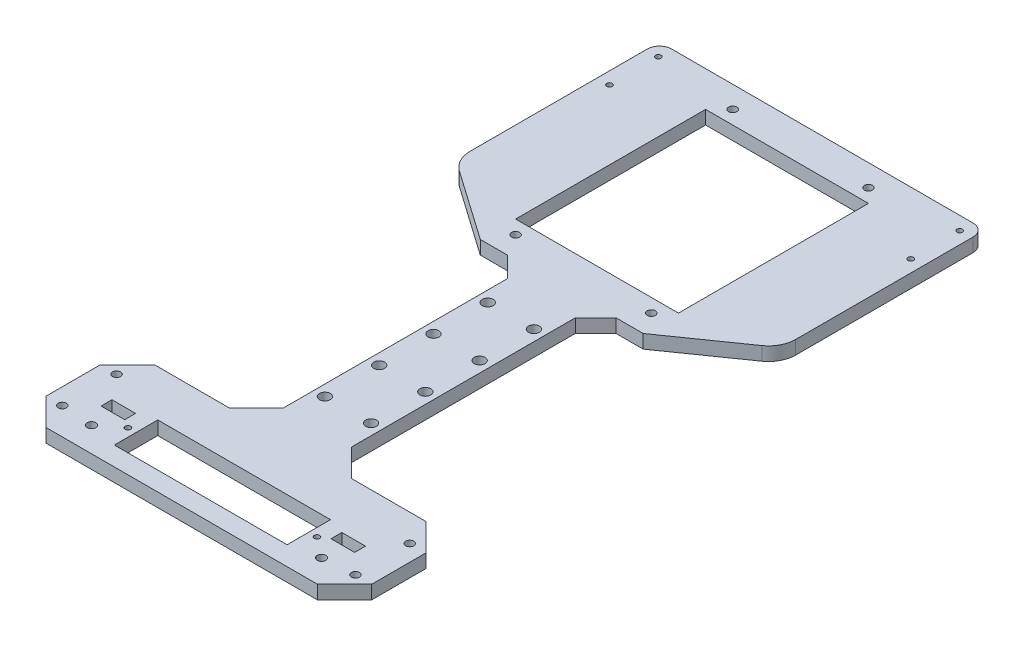
SolidWorks part; units mm, degrees
material "Acrílico (médio-alto impacto)"
ref_plane "Plano frontal" through (0, 0, 0) normal (0, 0, 1) x (1, 0, 0)
ref_plane "Plano superior" through (0, 0, 0) normal (0, 1, 0) x (1, 0, 0)
ref_plane "Plano direito" through (0, 0, 0) normal (1, 0, 0) x (0, 0, -1)
sketch "Esboço1" plane through (0, 0, 0) normal (0, 1, 0) x (1, 0, 0)
  line L0 (-18.0889, 17.9415) -> (-18.0889, 19.4415)
  line L1 (-13.5889, 23.9415) -> (97.4111, 23.9415)
  line L2 (-18.0889, 17.9415) -> (-18.0889, -45.8529)
  line L3 (-13.8247, -54.0444) -> (11.9111, -72.0648)
  line L4 (11.9111, -72.0648) -> (21.9111, -72.0648)
  line L5 (41.9111, -1077.9191) -> (41.9111, -72.0648) construction
  line L7 (97.6469, -54.0444) -> (71.9111, -72.0648)
  line L9 (101.9111, 17.9415) -> (101.9111, -45.8529)
  line L10 (101.9111, 17.9415) -> (101.9111, 19.4415)
  line L11 (21.9111, -72.0648) -> (29.4111, -79.5648)
  line L12 (29.4111, -79.5648) -> (29.4111, -162.0648)
  line L13 (29.4111, -162.0648) -> (19.4111, -172.0648)
  line L14 (19.4111, -172.0648) -> (-8.0889, -172.0648)
  line L15 (-18.0889, -182.0648) -> (-18.0889, -202.0648)
  line L16 (-8.0889, -212.0648) -> (91.9111, -212.0648)
  line L17 (-18.0889, -202.0648) -> (-8.0889, -212.0648)
  line L18 (-8.0889, -172.0648) -> (-18.0889, -182.0648)
  line L19 (71.9111, -72.0648) -> (61.9111, -72.0648)
  line L20 (41.9111, 23.9415) -> (41.9111, 1029.7958) construction
  line L21 (61.9111, -72.0648) -> (54.4111, -79.5648)
  line L22 (91.9111, -172.0648) -> (101.9111, -182.0648)
  line L23 (101.9111, -202.0648) -> (91.9111, -212.0648)
  line L24 (101.9111, -182.0648) -> (101.9111, -202.0648)
  line L25 (64.4111, -172.0648) -> (91.9111, -172.0648)
  line L26 (54.4111, -162.0648) -> (64.4111, -172.0648)
  line L27 (54.4111, -79.5648) -> (54.4111, -162.0648)
  arc A0 (-13.5889, 23.9415) -> (-18.0889, 19.4415) centre (-13.5889, 19.4415) ccw
  arc A1 (97.4111, 23.9415) -> (101.9111, 19.4415) centre (97.4111, 19.4415) cw
  arc A2 (97.6469, -54.0444) -> (101.9111, -45.8529) centre (91.9111, -45.8529) ccw
  arc A3 (-18.0889, -45.8529) -> (-13.8247, -54.0444) centre (-8.0889, -45.8529) ccw
  point P10 (101.9111, -51.0585)
  point P18 (-18.0889, -51.0585)
  point P20 (41.9111, -72.0648)
  point P22 (41.9111, 23.9415)
  point P26 (-18.0889, -212.0648)
  point P28 (-18.0889, -172.0648)
  point P37 (41.9111, -212.0648)
  point P43 (101.9111, -172.0648)
  point P44 (101.9111, -212.0648)
  dimension "D5" = 10
  dimension "D1" = 75
  dimension "D2" = 125
  dimension "D3" = 30
  dimension "D4" = 45
  dimension "D6" = 120
  dimension "D7" = 25
  dimension "D8" = 90
  dimension "D9" = 45
  dimension "D10" = 10
  dimension "D11" = 180
  dimension "D12" = 40
extrude "Base " add sketch "Esboço1" along normal blind 5 contours L9 A2 L7 L19 L21 L27 L26 L25 L22 L24 L23 L16 L17 L15 L18 L14 L13 L12 L11 L4 L3 A3 L2 L0 A0 L1 A1 L10
sketch "Esboço2" plane through (0, 5, 0) normal (0, 1, 0) x (1, 0, 0)
  line L0 (-13.5889, 23.9415) -> (97.4111, 23.9415) construction
  line L1 (-18.0889, -45.8529) -> (-18.0889, 19.4415) construction
  line L2 (41.9111, 23.9415) -> (41.9111, -27.3922) construction
  circle A0 centre (-13.5889, 19.0215) radius 1
  circle A1 centre (-13.5889, 1.0215) radius 1
  circle A2 centre (97.4111, 1.0215) radius 1
  circle A3 centre (97.4111, 19.0215) radius 1
  dimension "D1" = 4.92
  dimension "D2" = 4.5
  dimension "D3" = 2
  dimension "D4" = 2
  dimension "D5" = 4.5
  dimension "D6" = 18
extrude "Furo Bracket Motor" cut sketch "Esboço2" against normal blind 3
sketch "Esboço4" plane through (0, 0, 0) normal (0, -1, 0) x (1, 0, 0)
  line L1 (11.9111, 59.0635) -> (71.9111, 59.0635)
  line L2 (11.9111, 59.0635) -> (11.9111, -10.9365)
  line L3 (11.9111, -10.9365) -> (71.9111, -10.9365)
  line L4 (71.9111, 59.0635) -> (71.9111, -10.9365)
  line L5 (101.9111, -19.4415) -> (101.9111, 45.8529) construction
  line L7 (-13.5889, -23.9415) -> (97.4111, -23.9415) construction
  line L8 (-18.0889, -19.4415) -> (-18.0889, 45.8529) construction
  dimension "D1" = 60
  dimension "D2" = 70
  dimension "D3" = 30
  dimension "D4" = 13.005
  dimension "D5" = 30
extrude "Encaixe PCB" cut sketch "Esboço4" against normal through all
sketch "Esboço6" plane through (0, 0, 0) normal (0, -1, 0) x (1, 0, 0)
  line L0 (71.9111, 59.0635) -> (11.9111, 59.0635) construction
  line L1 (11.9111, 59.0635) -> (11.9111, -10.9365) construction
  line L2 (71.9111, -10.9365) -> (71.9111, 59.0635) construction
  line L3 (11.9111, -10.9365) -> (71.9111, -10.9365) construction
  circle A0 centre (16.9111, 64.0635) radius 1.5
  circle A1 centre (66.9111, 64.0635) radius 1.5
  circle A2 centre (66.9111, -15.9365) radius 1.5
  circle A3 centre (16.9111, -15.9365) radius 1.5
  dimension "D1" = 5
  dimension "D2" = 5
  dimension "D3" = 5
  dimension "D4" = 5
  dimension "D5" = 5
  dimension "D6" = 5
  dimension "D7" = 5
  dimension "D8" = 5
  dimension "D9" = 3
  dimension "D10" = 3
  dimension "D11" = 3
  dimension "D12" = 3
extrude "Parafuso PCB" cut sketch "Esboço6" against normal through all
sketch "Esboço7" plane through (0, 0, 0) normal (0, -1, 0) x (1, 0, 0)
  line L0 (29.4111, 79.5648) -> (29.4111, 162.0648) construction
  line L1 (41.9111, 212.0648) -> (41.9111, -23.9415) construction
  circle A0 centre (33.4111, 90.8148) radius 2
  circle A1 centre (33.4111, 110.8148) radius 2
  circle A2 centre (33.4111, 130.8148) radius 2
  circle A3 centre (33.4111, 150.8148) radius 2
  circle A4 centre (50.4111, 150.8148) radius 2
  circle A5 centre (50.4111, 130.8148) radius 2
  circle A6 centre (50.4111, 110.8148) radius 2
  circle A7 centre (50.4111, 90.8148) radius 2
  dimension "D1" = 11.25
  dimension "D2" = 20
  dimension "D3" = 20
  dimension "D4" = 20
  dimension "D5" = 11.25
  dimension "D6" = 4
  dimension "D7" = 4
  dimension "D8" = 4
  dimension "D9" = 4
  dimension "D10" = 4
  dimension "D11" = 4
extrude "Enforca Gato" cut sketch "Esboço7" against normal through all
sketch "Esboço8" plane through (0, 0, 0) normal (0, -1, 0) x (1, 0, 0)
  line L0 (41.9111, 212.0648) -> (41.9111, 196.2813) construction
  circle A0 centre (95.9111, 182.0648) radius 1.5
  circle A1 centre (95.9111, 202.0648) radius 1.5
  circle A2 centre (-12.0889, 202.0648) radius 1.5
  circle A3 centre (-12.0889, 182.0648) radius 1.5
  dimension "D1" = 10
  dimension "D2" = 6
  dimension "D3" = 3
  dimension "D4" = 10
  dimension "D5" = 6
  dimension "D6" = 3
extrude "Parafuso Apoio" cut sketch "Esboço8" against normal blind 10
sketch "Esboço9" plane through (0, 5, 0) normal (0, 1, 0) x (1, 0, 0)
  line L0 (41.9111, -212.0648) -> (41.9111, -165.8319) construction
  line L1 (-18.0889, -182.0648) -> (-18.0889, -202.0648) construction
  line L2 (101.9111, -182.0648) -> (101.9111, -202.0648) construction
  line L3 (-8.0889, -212.0648) -> (91.9111, -212.0648) construction
  line L4 (19.4111, -172.0648) -> (-8.0889, -172.0648) construction
  line L5 (73.7311, -205.0648) -> (10.0911, -205.0648)
  line L6 (73.7311, -205.0648) -> (73.7311, -189.0648)
  line L7 (73.7311, -189.0648) -> (10.0911, -189.0648)
  line L8 (10.0911, -205.0648) -> (10.0911, -189.0648)
  line L9 (3.9111, -195.0648) -> (-4.7889, -195.0648)
  line L10 (3.9111, -195.0648) -> (3.9111, -191.0648)
  line L11 (3.9111, -191.0648) -> (-4.7889, -191.0648)
  line L12 (-4.7889, -195.0648) -> (-4.7889, -191.0648)
  line L13 (88.6111, -195.0648) -> (88.6111, -191.0648)
  line L14 (79.9111, -191.0648) -> (88.6111, -191.0648)
  line L15 (79.9111, -195.0648) -> (79.9111, -191.0648)
  line L16 (79.9111, -195.0648) -> (88.6111, -195.0648)
  circle A0 centre (76.7311, -197.0648) radius 1
  circle A1 centre (7.0911, -197.0648) radius 1
  circle A2 centre (-0.4389, -202.9248) radius 1.6
  circle A3 centre (84.2611, -202.9248) radius 1.6
  dimension "D1" = 69.64
  dimension "D2" = 25.18
  dimension "D3" = 25.18
  dimension "D4" = 15
  dimension "D5" = 15
  dimension "D6" = 2
  dimension "D7" = 2
  dimension "D12" = 7.86
  dimension "D13" = 4.35
  dimension "D17" = 3.2
  dimension "D8" = 7
  dimension "D9" = 3
  dimension "D10" = 3
  dimension "D11" = 16
  dimension "D14" = 4.35
  dimension "D15" = 8.7
  dimension "D16" = 4
  dimension "D18" = 13.3
  dimension "D19" = 19
extrude "Corte-extrusão1" cut sketch "Esboço9" against normal blind 10
